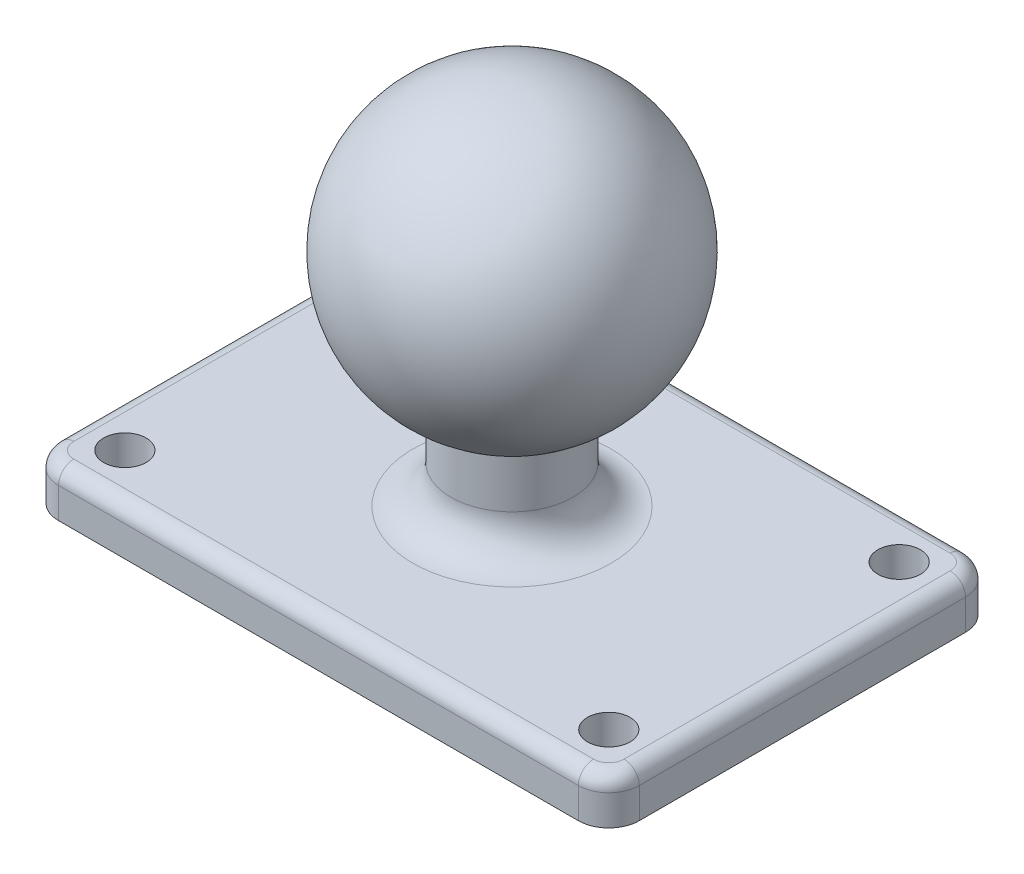
SolidWorks part; units mm, degrees
ref_plane "Front Plane" through (0, 0, 0) normal (0, 0, 1) x (1, 0, 0)
ref_plane "Top Plane" through (0, 0, 0) normal (0, 1, 0) x (1, 0, 0)
ref_plane "Right Plane" through (0, 0, 0) normal (1, 0, 0) x (0, 0, -1)
sketch "Sketch1" plane through (0, 0, 0) normal (0, 1, 0) x (1, 0, 0)
  line L1 (-34.1, -25.4) -> (34.1, -25.4)
  line L2 (-38.1, -21.4) -> (-38.1, 21.4)
  line L3 (-34.1, 25.4) -> (34.1, 25.4)
  line L4 (38.1, -21.4) -> (38.1, 21.4)
  line L5 (-38.1, 0) -> (38.1, 0) construction
  line L6 (0, 25.4) -> (0, -25.4) construction
  circle A0 centre (-31.75, 19.05) radius 2.794
  circle A1 centre (31.75, 19.05) radius 2.794
  circle A2 centre (31.75, -19.05) radius 2.794
  circle A3 centre (-31.75, -19.05) radius 2.794
  arc A4 (34.1, 25.4) -> (38.1, 21.4) centre (34.1, 21.4) cw
  arc A5 (38.1, -21.4) -> (34.1, -25.4) centre (34.1, -21.4) cw
  arc A6 (-34.1, -25.4) -> (-38.1, -21.4) centre (-34.1, -21.4) cw
  arc A7 (-38.1, 21.4) -> (-34.1, 25.4) centre (-34.1, 21.4) cw
  point P0 (0, 0)
  point P17 (0, 0)
  point P20 (38.1, 25.4)
  point P25 (-38.1, -25.4)
  point P30 (-38.1, 25.4)
  dimension "D4" = 38.1
  dimension "D7" = 5.588
  dimension "D8" = 4
  dimension "D1" = 76.2
  dimension "D2" = 50.8
  dimension "D3" = 63.5
  dimension "D5" = 19.05
  dimension "D6" = 31.75
extrude "Boss-Extrude1" add sketch "Sketch1" along normal blind 6
sketch "Sketch2" plane through (0, 0, 0) normal (0, 0, 1) x (1, 0, 0)
  line L0 (0, 6) -> (0, 54.0228)
  line L1 (-34.1, 6) -> (34.1, 6) construction
  line L2 (0, 6) -> (-8, 6)
  line L3 (-8, 6) -> (-8, 17.684)
  arc A0 (0, 54.0228) -> (-8, 17.684) centre (0, 34.9728) ccw
  dimension "D2" = 38.1
  dimension "D1" = 11.684
  dimension "D3" = 8
revolve "Revolve1" add sketch "Sketch2" angle 360 about L0
fillet "Fillet1" radius 5 1 edges at (0, 6, -8)
fillet "Fillet2" radius 2 8 edges at (-36.9284, 6, 24.2284) (-38.1, 6, 0) (-36.9284, 6, -24.2284) (0, 6, -25.4) (36.9284, 6, -24.2284) (38.1, 6, 0) (36.9284, 6, 24.2284) (0, 6, 25.4)
